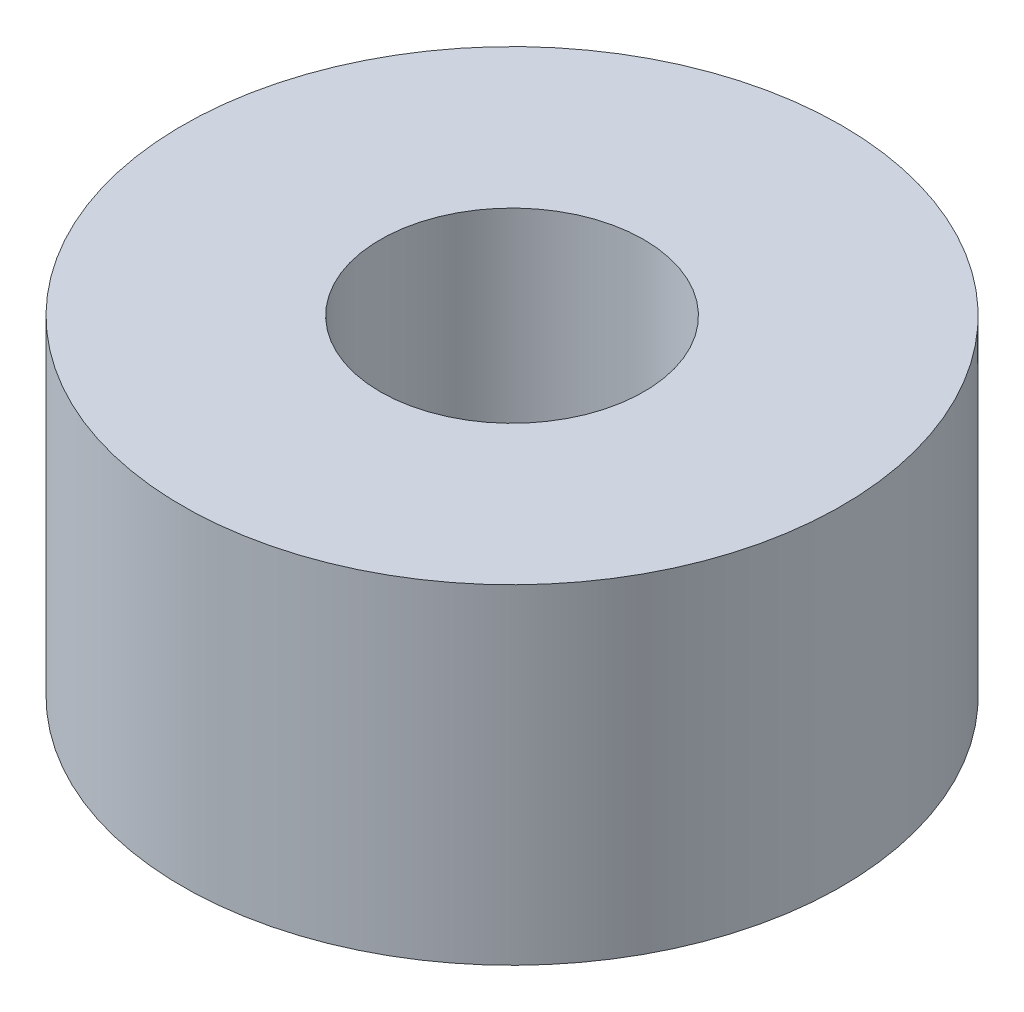
SolidWorks part; units mm, degrees
ref_plane "前视基准面" through (0, 0, 0) normal (0, 0, 1) x (1, 0, 0)
ref_plane "上视基准面" through (0, 0, 0) normal (0, 1, 0) x (1, 0, 0)
ref_plane "右视基准面" through (0, 0, 0) normal (1, 0, 0) x (0, 0, -1)
sketch "草图1" plane through (0, 0, 0) normal (0, 0, 1) x (1, 0, 0)
  line L0 (2.5, 2.5) -> (1, 2.5)
  line L1 (1, 2.5) -> (1, 0)
  line L2 (1, 0) -> (2.5, 0)
  line L3 (2.5, 0) -> (2.5, 2.5)
  line L4 (0, 2.5) -> (0, 0) construction
revolve "旋转1" add sketch "草图1" angle 360 about L4
